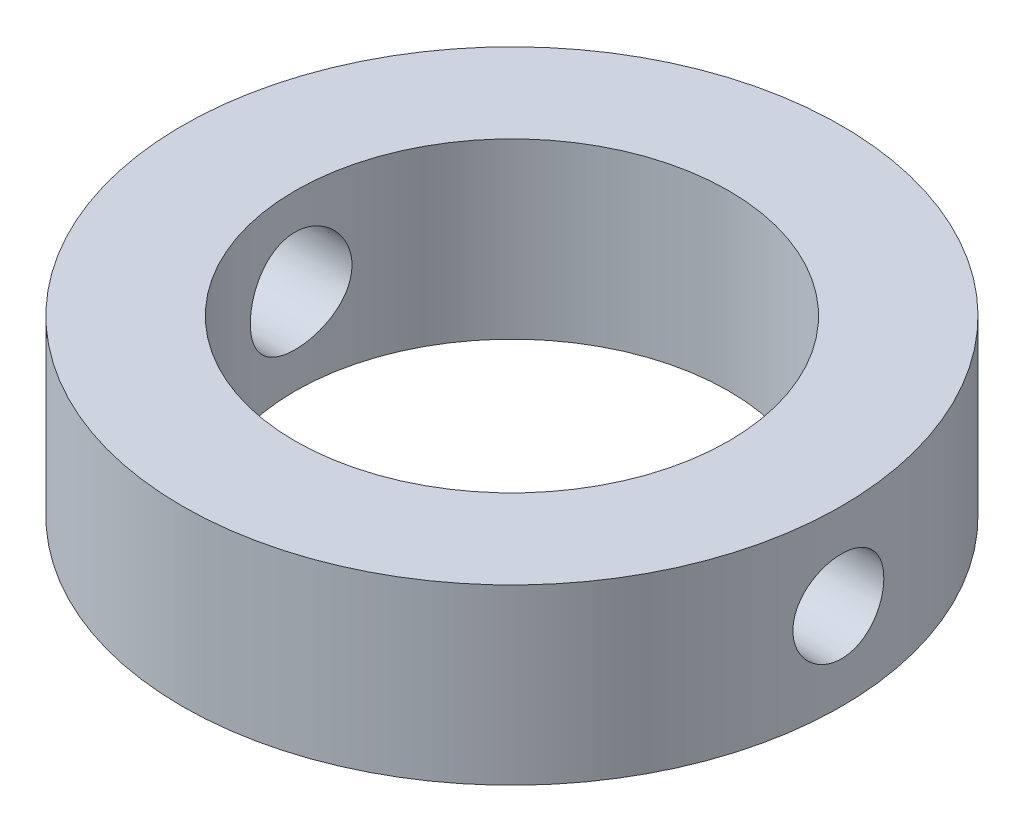
SolidWorks part; units mm, degrees
ref_plane "Front Plane" through (0, 0, 0) normal (0, 0, 1) x (1, 0, 0)
ref_plane "Top Plane" through (0, 0, 0) normal (0, 1, 0) x (1, 0, 0)
ref_plane "Right Plane" through (0, 0, 0) normal (1, 0, 0) x (0, 0, -1)
sketch "Sketch1" plane through (0, 0, 0) normal (0, 1, 0) x (1, 0, 0)
  circle A0 centre (0, 0) radius 19
  circle A1 centre (0, 0) radius 12.5
  dimension "D1" = 38
  dimension "D2" = 25
extrude "Boss-Extrude1" add sketch "Sketch1" along normal mid plane 10
sketch "Sketch2" plane through (0, 0, 0) normal (0, 0, 1) x (1, 0, 0)
  line L0 (0, 0) -> (50000, 0) construction
  line L1 (-19, 0) -> (-19, 3)
  line L2 (-19, 3) -> (19, 2.62)
  line L3 (19, 2.62) -> (19, 0)
  line L4 (-19, 0) -> (19, 0)
  line L5 (-19, 5) -> (-19, -5) construction
  line L6 (19, -5) -> (19, 5) construction
  dimension "D1" = 6
  dimension "D2" = 5.24
revolve "Cut-Revolve1" cut sketch "Sketch2" angle 360 about L0
